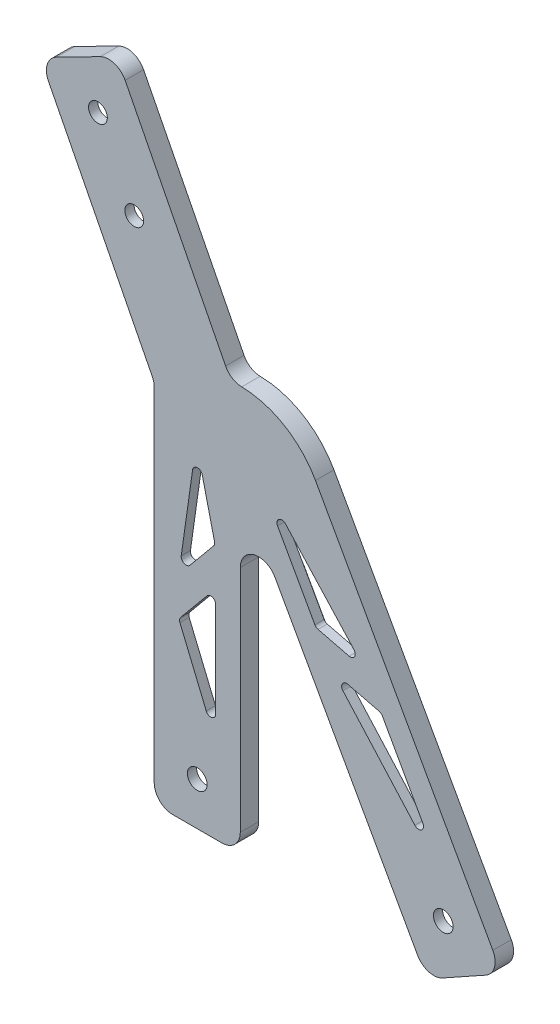
SolidWorks part; units mm, degrees
ref_plane "Piano frontale" through (0, 0, 0) normal (0, 0, 1) x (1, 0, 0)
ref_plane "Piano superiore" through (0, 0, 0) normal (0, 1, 0) x (1, 0, 0)
ref_plane "Piano destro" through (0, 0, 0) normal (1, 0, 0) x (0, 0, -1)
sketch "Schizzo1" plane through (0, 0, 0) normal (0, 0, 1) x (1, 0, 0)
  line L0 (24.8598, 72.2692) -> (24.8598, 64.136) construction
  line L1 (35.424, 75.3104) -> (27.901, 75.3104) construction
  line L2 (38.4652, 65.3753) -> (38.4652, 72.2692) construction
  line L3 (19.3201, 59.2171) -> (14.402, 59.2171) construction
  line L4 (79.5779, 59.2171) -> (47.7896, 59.2171) construction
  line L5 (9.5392, 51.6024) -> (20.0564, 26.3839) construction
  line L6 (24.8598, 72.2692) -> (24.8598, 64.136)
  line L7 (35.424, 75.3104) -> (27.901, 75.3104)
  line L8 (38.4652, 65.3753) -> (38.4652, 72.2692)
  line L9 (19.3201, 59.2171) -> (14.402, 59.2171)
  line L10 (79.5779, 59.2171) -> (47.7896, 59.2171)
  line L11 (9.5392, 51.6024) -> (20.0564, 26.3839)
  circle A0 centre (17.8355, 52.4568) radius 1.6 construction
  circle A1 centre (57.8355, 52.4568) radius 1.6 construction
  circle A2 centre (17.8355, 52.4568) radius 1.6
  circle A3 centre (57.8355, 52.4568) radius 1.6
  circle A4 centre (53.5286, 55.0838) radius 1.6 construction
  circle A5 centre (62.0658, 49.8765) radius 1.6 construction
  circle A6 centre (13.5679, 53.3113) radius 1.6 construction
  circle A7 centre (22.103, 51.6024) radius 1.6 construction
  circle A8 centre (53.5286, 55.0838) radius 1.6
  circle A9 centre (62.0658, 49.8765) radius 1.6
  circle A10 centre (13.5679, 53.3113) radius 1.6
  circle A11 centre (22.103, 51.6024) radius 1.6
sketch "Schizzo2" plane through (0, 0, 0) normal (0, 0, 1) x (1, 0, 0)
  line L0 (22.103, 51.6024) -> (13.5679, 53.3113) construction
  line L1 (1.6887, 138.2484) -> (7.5906, 126.6653) construction
  line L2 (10.8355, 45.4568) -> (10.8355, 104.8781)
  line L3 (1.6887, 138.2484) -> (-28.3966, 202.7666) construction
  line L4 (14.402, 59.2171) -> (246.1332, 167.2752) construction
  line L5 (79.5779, 59.2171) -> (47.7896, 59.2171) construction
  line L6 (1.6887, 138.2484) -> (-1.4892, 144.4854) construction
  line L7 (17.8355, 45.4568) -> (17.8355, 87.1016) construction
  line L8 (-7.7262, 141.3075) -> (10.8355, 104.8781)
  line L9 (10.8355, 45.4568) -> (24.8355, 45.4568)
  line L10 (24.8355, 45.4568) -> (24.8355, 97.296)
  line L11 (67.3576, 49.7495) -> (37.0649, 104.1108)
  line L12 (24.8355, 45.4568) -> (17.8355, 52.4568) construction
  line L13 (-7.7262, 141.3075) -> (4.7479, 147.6634)
  line L14 (1.6887, 138.2484) -> (4.7479, 147.6634) construction
  line L15 (24.8355, 97.296) -> (55.1282, 42.9347)
  line L16 (57.8355, 52.4568) -> (41.9431, 80.9761) construction
  line L17 (57.8355, 52.4568) -> (55.1282, 42.9347) construction
  line L18 (4.7479, 147.6634) -> (23.3199, 111.2137)
  line L19 (55.1282, 42.9347) -> (67.3576, 49.7495)
  line L20 (24.8598, 72.2692) -> (24.8598, 64.136) construction
  line L21 (24.8355, 97.296) -> (37.0649, 104.1108) construction
  circle A0 centre (17.8355, 52.4568) radius 1.6 construction
  circle A1 centre (57.8355, 52.4568) radius 1.6 construction
  circle A2 centre (17.8355, 52.4568) radius 1.6
  circle A3 centre (57.8355, 52.4568) radius 1.6
  circle A4 centre (1.6887, 138.2484) radius 1.525
  circle A5 centre (7.5906, 126.6653) radius 1.525
  arc A7 (37.0649, 104.1108) -> (23.3199, 111.2137) centre (24.8355, 97.296) ccw
  point P3 (4.6397, 132.4568)
  dimension "D5" = 3.05
  dimension "D6" = 13
  dimension "D7" = 14
  dimension "D8" = 80
  dimension "D1" = 25
  dimension "D2" = 2
  dimension "D3" = 45
  dimension "D4" = 45
  dimension "D9" = 45
  dimension "D10" = 14
extrude "Estrusione-Estrusione1" add sketch "Schizzo2" along normal blind 1.5
fillet "Raccordo1" radius 3 9 edges at (24.8355, 97.296, 0.75) (55.1282, 42.9347, 0.75) (24.8355, 45.4568, 0.75) (-7.7262, 141.3075, 0.75) (4.7479, 147.6634, 0.75) (10.8355, 104.8781, 0.75) (10.8355, 45.4568, 0.75) (67.3576, 49.7495, 0.75) (23.3199, 111.2137, 0.75)
sketch "Schizzo3" plane through (0, 0, 0) normal (0, 0, -1) x (-1, 0, 0)
  line L0 (-58.0329, 58.2656) -> (-47.7601, 76.7004)
  line L1 (-47.7601, 76.7004) -> (-39.7991, 78.6606)
  line L2 (-39.7991, 78.6606) -> (-58.0329, 58.2656)
  line L3 (-45.0995, 81.475) -> (-37.1385, 83.4352)
  line L4 (-37.1385, 83.4352) -> (-27.5762, 100.595)
  line L5 (-27.5762, 100.595) -> (-45.0995, 81.475)
  line L6 (-14.8355, 73.5133) -> (-20.8355, 59.0806)
  line L7 (-20.8355, 59.0806) -> (-20.8355, 80.7548)
  line L8 (-20.8355, 80.7548) -> (-14.8355, 73.5133)
  line L9 (-20.7369, 86.9053) -> (-17.6753, 99.8118)
  line L10 (-17.6753, 99.8118) -> (-14.8355, 79.7828)
  line L11 (-14.8355, 79.7828) -> (-20.7369, 86.9053)
  line L12 (-24.8355, 48.4568) -> (-24.8355, 85.7493) construction
  line L13 (-65.8972, 52.3701) -> (-37.0649, 104.1108) construction
  line L14 (-30.456, 87.2097) -> (-53.6678, 45.5553) construction
  line L15 (-10.8355, 104.1579) -> (-10.8355, 48.4568) construction
  line L16 (-30.456, 87.2097) -> (-53.6678, 45.5553) construction
  dimension "D1" = 4
  dimension "D2" = 4
  dimension "D3" = 4
  dimension "D4" = 4
  dimension "D5" = 4
  dimension "D6" = 4
  dimension "D7" = 4
  dimension "D8" = 4
  dimension "D9" = 4
extrude "Taglio-Estrusione1" cut sketch "Schizzo3" against normal through all
sketch "Schizzo4" plane through (0, 0, 0) normal (0, 0, -1) x (-1, 0, 0)
  line L0 (-35.3178, 103.1372) -> (-64.1502, 51.3966)
  line L1 (-63.7634, 50.0363) -> (-56.7752, 46.1421)
  line L2 (-55.4149, 46.5289) -> (-32.2031, 88.1832)
  line L3 (-22.8355, 85.7493) -> (-22.8355, 48.4568)
  line L4 (-21.8355, 47.4568) -> (-13.8355, 47.4568)
  line L5 (-12.8355, 48.4568) -> (-12.8355, 104.1579)
  line L6 (-12.2905, 106.4278) -> (4.5823, 139.5425)
  line L7 (4.1452, 140.8875) -> (-2.9828, 144.5194)
  line L8 (-4.3278, 144.0824) -> (-20.6625, 112.0237)
  line L9 (5.0532, 142.6695) -> (-2.0748, 146.3014)
  line L10 (-6.1098, 144.9903) -> (-22.4445, 112.9317)
  line L11 (-37.0649, 104.1108) -> (-65.8972, 52.3701)
  line L12 (-64.737, 48.2892) -> (-57.7487, 44.3951)
  line L13 (-53.6678, 45.5553) -> (-30.456, 87.2097)
  line L14 (-24.8355, 85.7493) -> (-24.8355, 48.4568)
  line L15 (-21.8355, 45.4568) -> (-13.8355, 45.4568)
  line L16 (-10.8355, 48.4568) -> (-10.8355, 104.1579)
  line L17 (-10.5085, 105.5199) -> (6.3643, 138.6345)
  line L18 (5.0532, 142.6695) -> (-2.0748, 146.3014)
  line L19 (-6.1098, 144.9903) -> (-22.4445, 112.9317)
  line L20 (-37.0649, 104.1108) -> (-65.8972, 52.3701)
  line L21 (-64.737, 48.2892) -> (-57.7487, 44.3951)
  line L22 (-53.6678, 45.5553) -> (-30.456, 87.2097)
  line L23 (-24.8355, 85.7493) -> (-24.8355, 48.4568)
  line L24 (-21.8355, 45.4568) -> (-13.8355, 45.4568)
  line L25 (-10.8355, 48.4568) -> (-10.8355, 104.1579)
  line L26 (-10.5085, 105.5199) -> (6.3643, 138.6345)
  arc A0 (-64.1502, 51.3966) -> (-63.7634, 50.0363) centre (-63.2767, 50.9098) ccw
  arc A1 (-56.7752, 46.1421) -> (-55.4149, 46.5289) centre (-56.2884, 47.0156) ccw
  arc A2 (-22.8355, 85.7493) -> (-32.2031, 88.1832) centre (-27.8355, 85.7493) ccw
  arc A3 (-22.8355, 48.4568) -> (-21.8355, 47.4568) centre (-21.8355, 48.4568) ccw
  arc A4 (-13.8355, 47.4568) -> (-12.8355, 48.4568) centre (-13.8355, 48.4568) ccw
  arc A5 (-12.2905, 106.4278) -> (-12.8355, 104.1579) centre (-7.8355, 104.1579) ccw
  arc A6 (4.5823, 139.5425) -> (4.1452, 140.8875) centre (3.6912, 139.9965) ccw
  arc A7 (-2.9828, 144.5194) -> (-4.3278, 144.0824) centre (-3.4368, 143.6284) ccw
  arc A8 (-25.0346, 109.2943) -> (-20.6625, 112.0237) centre (-25.1176, 114.2936) ccw
  arc A9 (-25.0346, 109.2943) -> (-35.3178, 103.1372) centre (-24.8355, 97.296) ccw
  arc A10 (-2.0748, 146.3014) -> (-6.1098, 144.9903) centre (-3.4368, 143.6284) ccw
  arc A11 (-25.0678, 111.2941) -> (-22.4445, 112.9317) centre (-25.1176, 114.2936) ccw
  arc A12 (-25.0678, 111.2941) -> (-37.0649, 104.1108) centre (-24.8355, 97.296) ccw
  arc A13 (-65.8972, 52.3701) -> (-64.737, 48.2892) centre (-63.2767, 50.9098) ccw
  arc A14 (-57.7487, 44.3951) -> (-53.6678, 45.5553) centre (-56.2884, 47.0156) ccw
  arc A15 (-24.8355, 85.7493) -> (-30.456, 87.2097) centre (-27.8355, 85.7493) ccw
  arc A16 (-24.8355, 48.4568) -> (-21.8355, 45.4568) centre (-21.8355, 48.4568) ccw
  arc A17 (-13.8355, 45.4568) -> (-10.8355, 48.4568) centre (-13.8355, 48.4568) ccw
  arc A18 (-10.5085, 105.5199) -> (-10.8355, 104.1579) centre (-7.8355, 104.1579) ccw
  arc A19 (6.3643, 138.6345) -> (5.0532, 142.6695) centre (3.6912, 139.9965) ccw
  arc A20 (-2.0748, 146.3014) -> (-6.1098, 144.9903) centre (-3.4368, 143.6284) ccw
  arc A21 (-25.0678, 111.2941) -> (-22.4445, 112.9317) centre (-25.1176, 114.2936) ccw
  arc A22 (-25.0678, 111.2941) -> (-37.0649, 104.1108) centre (-24.8355, 97.296) ccw
  arc A23 (-65.8972, 52.3701) -> (-64.737, 48.2892) centre (-63.2767, 50.9098) ccw
  arc A24 (-57.7487, 44.3951) -> (-53.6678, 45.5553) centre (-56.2884, 47.0156) ccw
  arc A25 (-24.8355, 85.7493) -> (-30.456, 87.2097) centre (-27.8355, 85.7493) ccw
  arc A26 (-24.8355, 48.4568) -> (-21.8355, 45.4568) centre (-21.8355, 48.4568) ccw
  arc A27 (-13.8355, 45.4568) -> (-10.8355, 48.4568) centre (-13.8355, 48.4568) ccw
  arc A28 (-10.5085, 105.5199) -> (-10.8355, 104.1579) centre (-7.8355, 104.1579) ccw
  arc A29 (6.3643, 138.6345) -> (5.0532, 142.6695) centre (3.6912, 139.9965) ccw
  dimension "D1" = 0
  dimension "D2" = 2
extrude "Estrusione-Estrusione2" add sketch "Schizzo4" along normal blind 1.5
fillet "Raccordo2" radius 0.8 12 edges at (17.6753, 99.8118, 0.75) (20.8355, 80.7548, 0.75) (14.8355, 73.5133, 0.75) (14.8355, 79.7828, 0.75) (20.7369, 86.9053, 0.75) (20.8355, 59.0806, 0.75) (58.0329, 58.2656, 0.75) (39.7991, 78.6606, 0.75) (47.7601, 76.7004, 0.75) (27.5762, 100.595, 0.75) (37.1385, 83.4352, 0.75) (45.0995, 81.475, 0.75)
